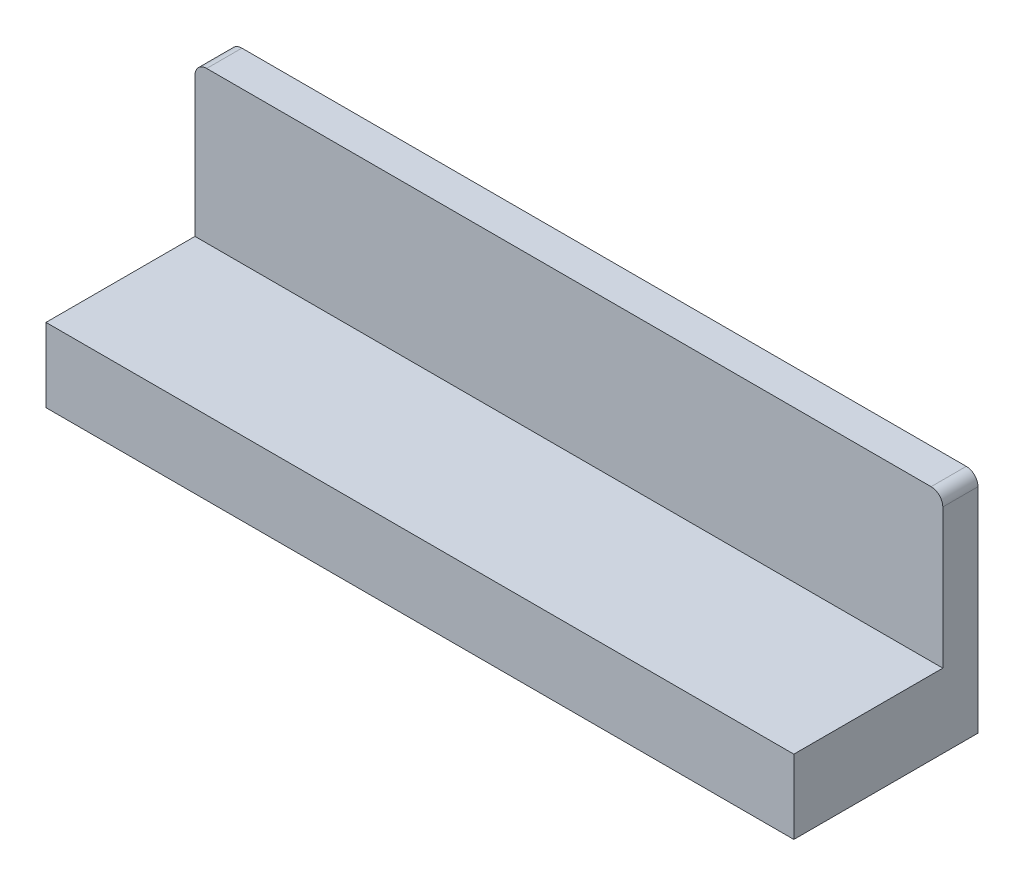
SolidWorks part; units mm, degrees
ref_plane "Front Plane" through (0, 0, 0) normal (0, 0, 1) x (1, 0, 0)
ref_plane "Top Plane" through (0, 0, 0) normal (0, 1, 0) x (1, 0, 0)
ref_plane "Right Plane" through (0, 0, 0) normal (1, 0, 0) x (0, 0, -1)
sketch "Sketch1" plane through (0, 0, 0) normal (1, 0, 0) x (0, 0, -1)
  line L0 (0, 0) -> (-7.85, 0)
  line L1 (-7.85, 0) -> (-7.85, 3.15)
  line L2 (-7.85, 3.15) -> (-1.5, 3.15)
  line L3 (-1.5, 3.15) -> (-1.5, 9.6)
  line L4 (-1.5, 9.6) -> (0, 9.6)
  line L5 (0, 9.6) -> (0, 0)
  dimension "D1" = 9.6
  dimension "D2" = 7.85
  dimension "D3" = 1.5
  dimension "D4" = 3.15
extrude "Boss-Extrude1" add sketch "Sketch1" against normal blind 31.88
fillet "Fillet1" radius 0.5 2 edges at (-31.88, 9.6, 0.75) (0, 9.6, 0.75)
shell "Shell1" thickness 1.5
sketch "Sketch2" plane through (0, 1.65, 0) normal (0, -1, 0) x (1, 0, 0)
  line L0 (-31.88, 0) -> (0, 0) construction
  line L3 (-31.88, 7.85) -> (-31.88, 0) construction
  circle A0 centre (-23.91, 3.925) radius 1.5
  circle A1 centre (-23.91, 3.925) radius 0.6
  circle A2 centre (-15.94, 3.925) radius 0.6
  circle A3 centre (-15.94, 3.925) radius 1.5
  circle A4 centre (-7.97, 3.925) radius 0.6
  circle A5 centre (-7.97, 3.925) radius 1.5
  dimension "D2" = 7.97
  dimension "D3" = 3
  dimension "D4" = 1.2
  dimension "D6" = 7.97
  dimension "D1" = 3.925
  dimension "D5" = 3
extrude "Boss-Extrude2" add sketch "Sketch2" along normal offset from surface (1.45 mm away) 0.2 up to face at (-15.94, 0, 3.925)
